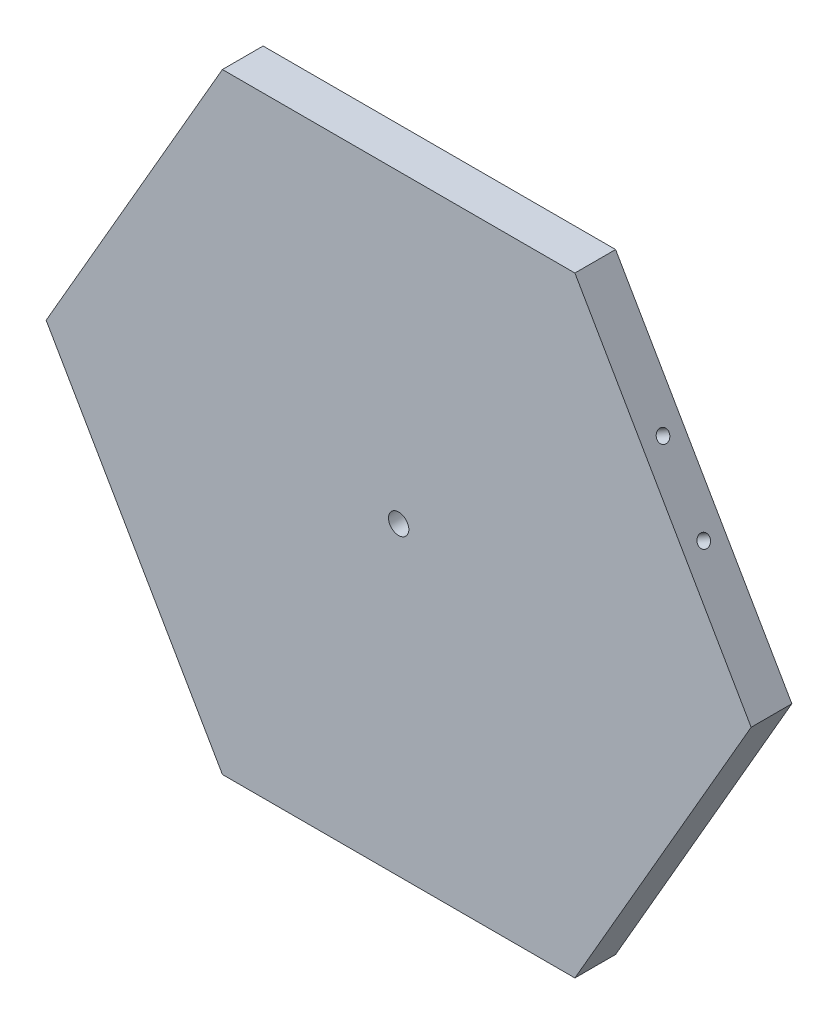
SolidWorks part; units mm, degrees
ref_plane "Front Plane" through (0, 0, 0) normal (0, 0, 1) x (1, 0, 0)
ref_plane "Top Plane" through (0, 0, 0) normal (0, 1, 0) x (1, 0, 0)
ref_plane "Right Plane" through (0, 0, 0) normal (1, 0, 0) x (0, 0, -1)
sketch "Sketch1" plane through (0, 0, 0) normal (0, 0, 1) x (1, 0, 0)
  line L1 (86.6025, 0) -> (43.3013, 75)
  line L2 (43.3013, 75) -> (-43.3013, 75)
  line L3 (-43.3013, 75) -> (-86.6025, 0)
  line L4 (-86.6025, 0) -> (-43.3013, -75)
  line L5 (-43.3013, -75) -> (43.3013, -75)
  line L6 (43.3013, -75) -> (86.6025, 0)
  circle A0 centre (0, 0) radius 75 construction
  dimension "D1" = 150
extrude "Boss-Extrude1" add sketch "Sketch1" along normal mid plane 10
sketch "Sketch2" plane through (0, -75, 0) normal (0, -1, 0) x (1, 0, 0)
  line L0 (-43.3013, -5) -> (43.3013, -5) construction
  circle A0 centre (-10, 0) radius 1.5
  circle A1 centre (10, 0) radius 1.5
  dimension "D1" = 3
  dimension "D2" = 10
  dimension "D3" = 10
  dimension "D4" = 5
extrude "Cut-Extrude1" cut sketch "Sketch2" against normal blind 10
sketch "Sketch3" plane through (0, 0, 5) normal (0, 0, 1) x (1, 0, 0)
  circle A0 centre (0, 0) radius 2.5
  dimension "D1" = 5
extrude "Cut-Extrude2" cut sketch "Sketch3" against normal blind 10
pattern_circular "CirPattern1" count 3 over 360 about axis through (0, 0, 0) along (0, 0, 1) of "Cut-Extrude1"
sketch "Sketch4" plane through (0, 0, 5) normal (0, 0, 1) x (1, 0, 0)
  line L0 (0, 0) -> (86.6025, 0) construction
  line L1 (0, 0) -> (64.9519, 37.5) construction
  line L2 (86.6025, 0) -> (43.3013, 75) construction
  line L3 (0, 0) -> (-64.9519, 37.5) construction
  line L4 (-43.3013, 75) -> (-86.6025, 0) construction
  line L5 (0, 0) -> (0, -75) construction
  line L6 (-43.3013, -75) -> (43.3013, -75) construction
  line L7 (64.9519, 37.5) -> (59.9519, 46.1603) construction
  line L8 (64.9519, 37.5) -> (69.9519, 28.8397) construction
  line L9 (-64.9519, 37.5) -> (-69.9519, 28.8397) construction
  line L10 (-64.9519, 37.5) -> (-59.9519, 46.1603) construction
  line L11 (0, -75) -> (-10, -75) construction
  line L12 (0, -75) -> (10, -75) construction
  line L13 (-69.9519, 28.8397) -> (0, 0)
  line L14 (0, 0) -> (-59.9519, 46.1603)
  line L15 (0, 0) -> (59.9519, 46.1603)
  line L16 (0, 0) -> (69.9519, 28.8397)
  line L17 (0, 0) -> (-10, -75)
  line L18 (0, 0) -> (10, -75)
  dimension "D1" = 10
  dimension "D2" = 10
  dimension "D3" = 10
  dimension "D4" = 10
  dimension "D5" = 10
  dimension "D6" = 10
  dimension "D7" = 22.405
  dimension "D8" = 37.595
  dimension "D9" = 142.405
  dimension "D10" = 157.595
  dimension "D11" = 262.405
  dimension "D12" = 277.595
